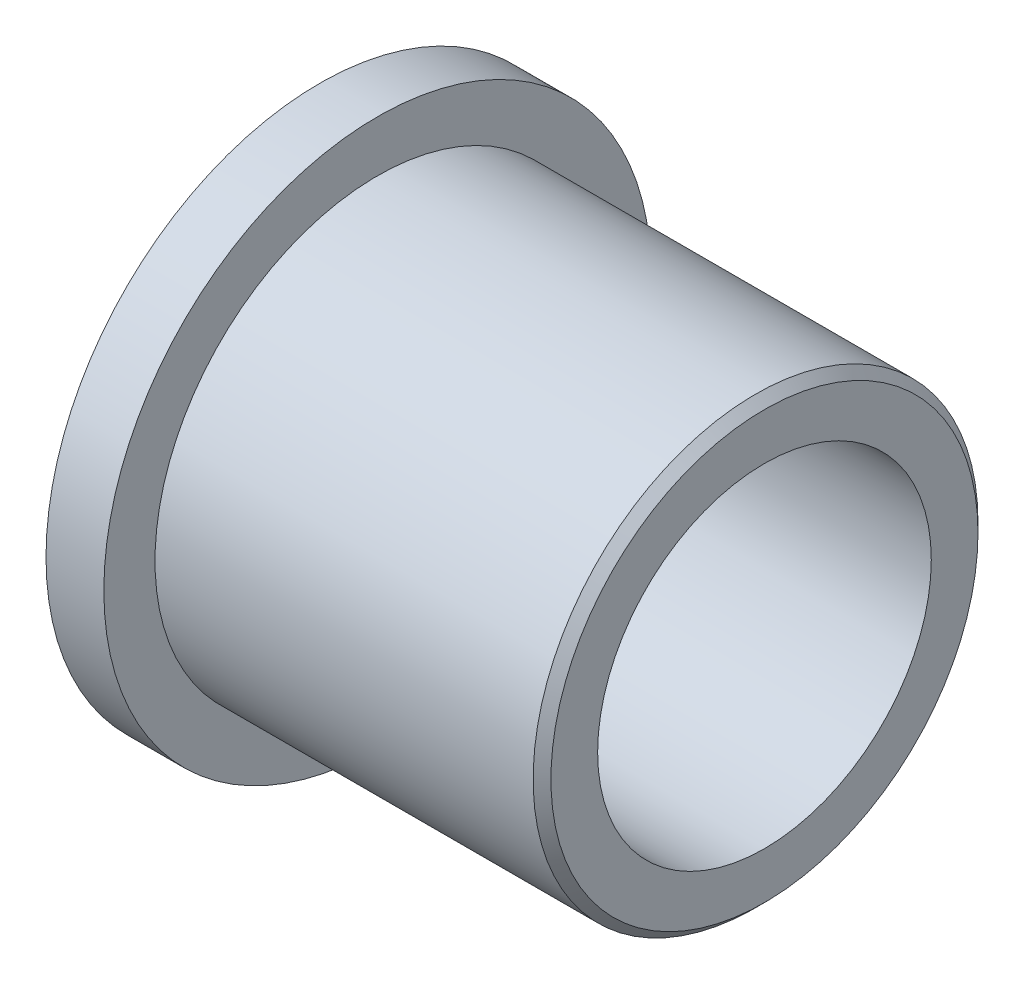
SolidWorks part; units mm, degrees
material "Brass"
ref_plane "Front Plane" through (0, 0, 0) normal (0, 0, 1) x (1, 0, 0)
ref_plane "Top Plane" through (0, 0, 0) normal (0, 1, 0) x (1, 0, 0)
ref_plane "Right Plane" through (0, 0, 0) normal (1, 0, 0) x (0, 0, -1)
sketch "Sketch1" plane through (0, 0, 0) normal (1, 0, 0) x (0, 0, -1)
  circle A0 centre (0, 0) radius 15.621
  dimension "D1" = 31.242
extrude "Boss-Extrude1" add sketch "Sketch1" along normal blind 3.302
sketch "Sketch2" plane through (3.302, 0, 0) normal (1, 0, 0) x (0, 0, -1)
  circle A0 centre (0, 0) radius 12.7
  dimension "D1" = 25.4
extrude "Boss-Extrude2" add sketch "Sketch2" along normal blind 22.098
hole_wizard "3/8 (0.75) Diameter Hole1" positions "Sketch3" profile "Sketch4" hole size "3/8" standard "ANSI Inch" end condition through all
sketch "Sketch3" plane through (25.4, 0, 0) normal (1, 0, 0) x (0, 0, -1)
  point P0 (0, 0)
sketch "Sketch4" plane through (25.4, 0, 0) normal (0, 1, 0) x (0, 0, -1)
  line L0 (0, 0) -> (0, 25.4)
  line L1 (0, 25.4) -> (9.525, 25.4)
  line L2 (9.525, 25.4) -> (9.525, 0)
  line L5 (9.525, 0) -> (0, 0)
  line L11 (0, -6.35) -> (0, 107.95) construction
  dimension "Thru Hole Dia." = 19.05
  dimension "Thru Hole Depth" = 25.4
chamfer "Chamfer1" distance 0.508 angle 45 1 edges at (25.4, 0, -12.7)
